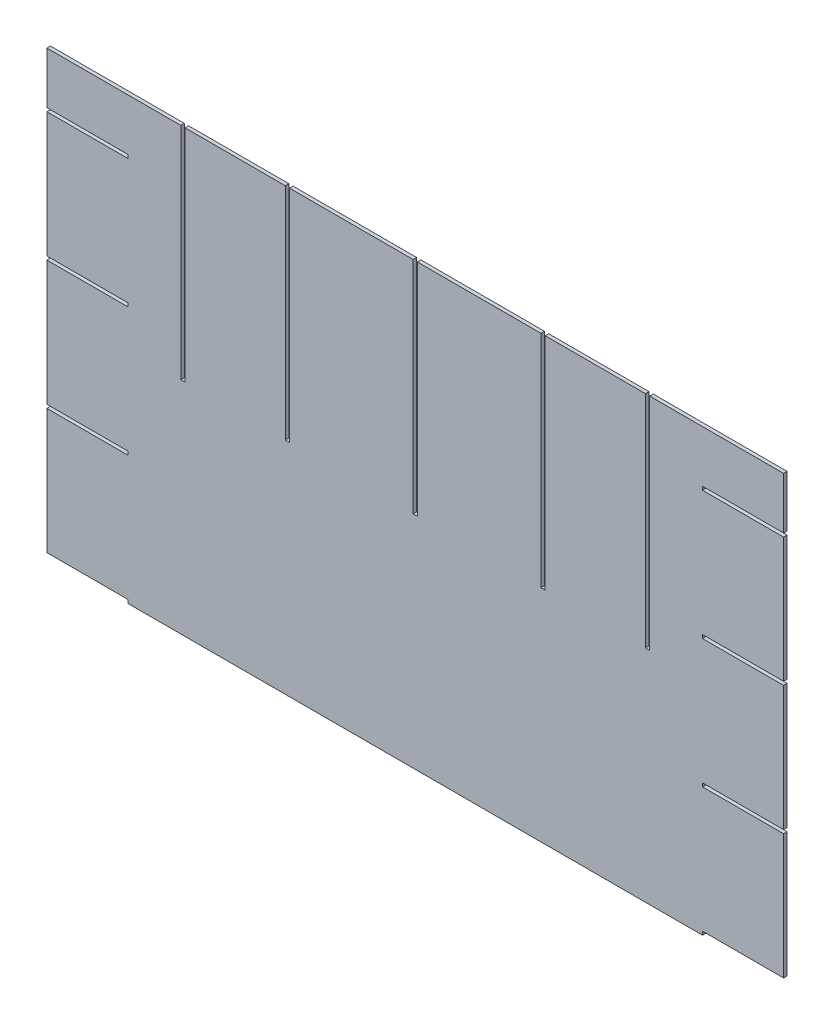
SolidWorks part; units mm, degrees
ref_plane "Front Plane" through (0, 0, 0) normal (0, 0, 1) x (1, 0, 0)
ref_plane "Top Plane" through (0, 0, 0) normal (0, 1, 0) x (1, 0, 0)
ref_plane "Right Plane" through (0, 0, 0) normal (1, 0, 0) x (0, 0, -1)
sketch "Model" plane through (0, 0, 0) normal (0, 0, 1) x (1, 0, 0)
  line L0 (-315.4413, 3) -> (-245.9797, 3)
  line L1 (-245.9797, 3) -> (-245.9797, 0)
  line L2 (-245.9797, 0) -> (245.9797, 0)
  line L3 (245.9797, 0) -> (245.9797, 3)
  line L4 (315.4413, 3) -> (245.9797, 3)
  line L5 (315.4413, 110) -> (315.4413, 3)
  line L6 (315.4413, 110) -> (245.9797, 110)
  line L7 (245.9797, 113) -> (245.9797, 110)
  line L8 (315.4413, 113) -> (245.9797, 113)
  line L9 (315.4413, 220) -> (315.4413, 113)
  line L10 (315.4413, 220) -> (245.9797, 220)
  line L11 (245.9797, 223) -> (245.9797, 220)
  line L12 (315.4413, 223) -> (245.9797, 223)
  line L13 (315.4413, 330) -> (315.4413, 223)
  line L14 (315.4413, 330) -> (245.9797, 330)
  line L15 (245.9797, 333) -> (245.9797, 330)
  line L16 (315.4413, 333) -> (245.9797, 333)
  line L17 (315.4413, 377.2207) -> (315.4413, 333)
  line L18 (315.4413, 377.2207) -> (200.7227, 377.2207)
  line L19 (200.7227, 188.6103) -> (200.7227, 377.2207)
  line L20 (197.1227, 188.6103) -> (200.7227, 188.6103)
  line L21 (197.1227, 377.2207) -> (197.1227, 188.6103)
  line L22 (197.1227, 377.2207) -> (111.3, 377.2207)
  line L23 (111.3, 188.6103) -> (111.3, 377.2207)
  line L24 (107.7, 188.6103) -> (111.3, 188.6103)
  line L25 (107.7, 377.2207) -> (107.7, 188.6103)
  line L26 (107.7, 377.2207) -> (1.8, 377.2207)
  line L27 (1.8, 188.6103) -> (1.8, 377.2207)
  line L28 (-1.8, 188.6103) -> (1.8, 188.6103)
  line L29 (-1.8, 377.2207) -> (-1.8, 188.6103)
  line L30 (-1.8, 377.2207) -> (-107.7, 377.2207)
  line L31 (-107.7, 188.6103) -> (-107.7, 377.2207)
  line L32 (-111.3, 188.6103) -> (-107.7, 188.6103)
  line L33 (-111.3, 377.2207) -> (-111.3, 188.6103)
  line L34 (-111.3, 377.2207) -> (-197.1227, 377.2207)
  line L35 (-197.1227, 188.6103) -> (-197.1227, 377.2207)
  line L36 (-200.7227, 188.6103) -> (-197.1227, 188.6103)
  line L37 (-200.7227, 377.2207) -> (-200.7227, 188.6103)
  line L38 (-200.7227, 377.2207) -> (-315.4413, 377.2207)
  line L39 (-315.4413, 377.2207) -> (-315.4413, 333)
  line L40 (-315.4413, 333) -> (-245.9797, 333)
  line L41 (-245.9797, 333) -> (-245.9797, 330)
  line L42 (-315.4413, 330) -> (-245.9797, 330)
  line L43 (-315.4413, 330) -> (-315.4413, 223)
  line L44 (-315.4413, 223) -> (-245.9797, 223)
  line L45 (-245.9797, 223) -> (-245.9797, 220)
  line L46 (-315.4413, 220) -> (-245.9797, 220)
  line L47 (-315.4413, 220) -> (-315.4413, 113)
  line L48 (-315.4413, 113) -> (-245.9797, 113)
  line L49 (-245.9797, 113) -> (-245.9797, 110)
  line L50 (-315.4413, 110) -> (-245.9797, 110)
  line L51 (-315.4413, 110) -> (-315.4413, 3)
extrude "Boss-Extrude1" add sketch "Model" along normal blind 3
